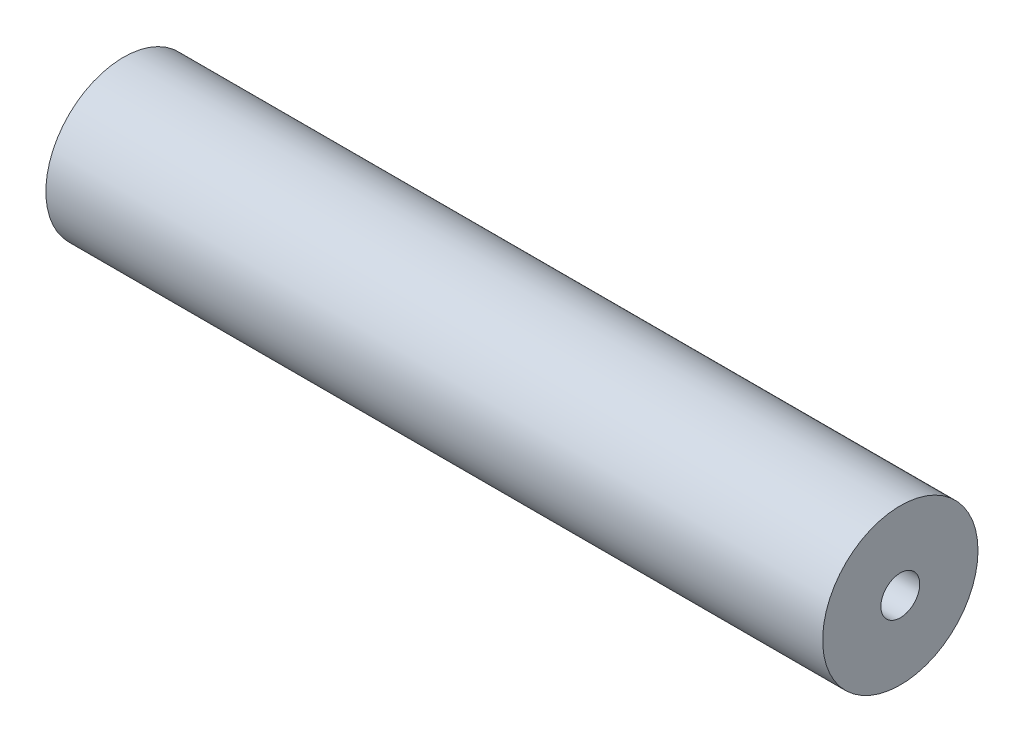
SolidWorks part; units mm, degrees
ref_plane "Front Plane" through (0, 0, 0) normal (0, 0, 1) x (1, 0, 0)
ref_plane "Top Plane" through (0, 0, 0) normal (0, 1, 0) x (1, 0, 0)
ref_plane "Right Plane" through (0, 0, 0) normal (1, 0, 0) x (0, 0, -1)
sketch "Sketch1" plane through (0, 0, 0) normal (1, 0, 0) x (0, 0, -1)
  circle A0 centre (0, 0) radius 25.4
extrude "Boss-Extrude1" add sketch "Sketch1" along normal blind 254
sketch "Sketch2" plane through (254, 0, 0) normal (1, 0, 0) x (0, 0, -1)
  circle A0 centre (0, 0) radius 6.35
extrude "Cut-Extrude1" cut sketch "Sketch2" against normal through all
